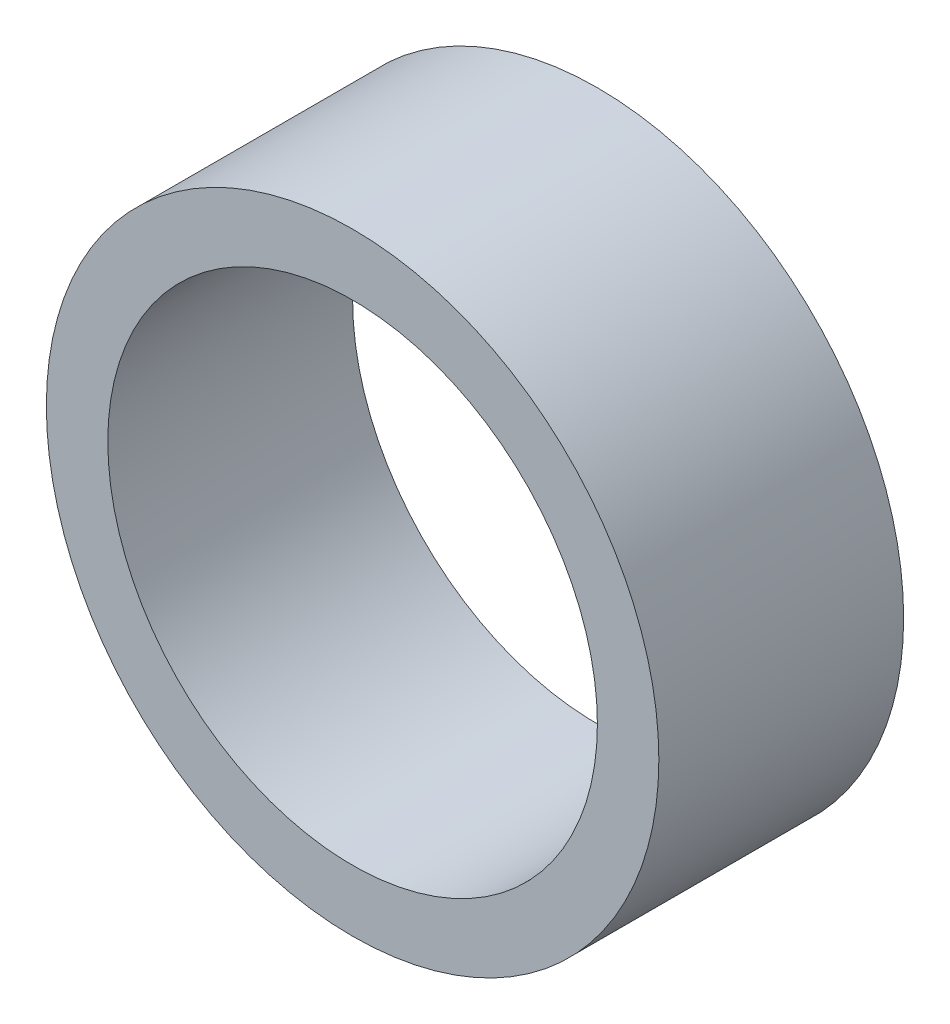
SolidWorks part; units mm, degrees
ref_plane "Front Plane" through (0, 0, 0) normal (0, 0, 1) x (1, 0, 0)
ref_plane "Top Plane" through (0, 0, 0) normal (0, 1, 0) x (1, 0, 0)
ref_plane "Right Plane" through (0, 0, 0) normal (1, 0, 0) x (0, 0, -1)
sketch "Sketch1" plane through (0, 0, 0) normal (0, 0, 1) x (1, 0, 0)
  circle A0 centre (0, 0) radius 15.8877
  circle A1 centre (0, 0) radius 12.7
  dimension "D1" = 31.7754
  dimension "ID" = 25.4
extrude "Extrude1" add sketch "Sketch1" along normal mid plane 12.7
sketch "Sketch2" plane through (0, 0, 0) normal (1, 0, 0) x (0, 0, -1)
  line L0 (-6.35, -12.7) -> (6.35, -12.7) construction
  line L3 (6.35, 12.7) -> (-6.35, 12.7) construction
  line L5 (-6.35, -12.7) -> (6.35, -12.7)
  line L6 (6.35, 12.7) -> (-6.35, 12.7)
sketch "Sketch4" plane through (0, 0, 6.35) normal (0, 0, 1) x (1, 0, 0)
  line L0 (0, 0) -> (-8.9803, 8.9803)
  line L1 (0, -3.4925) -> (0, 3.4925) construction
  circle A0 centre (0, 0) radius 12.7 construction
  dimension "D1" = 45
